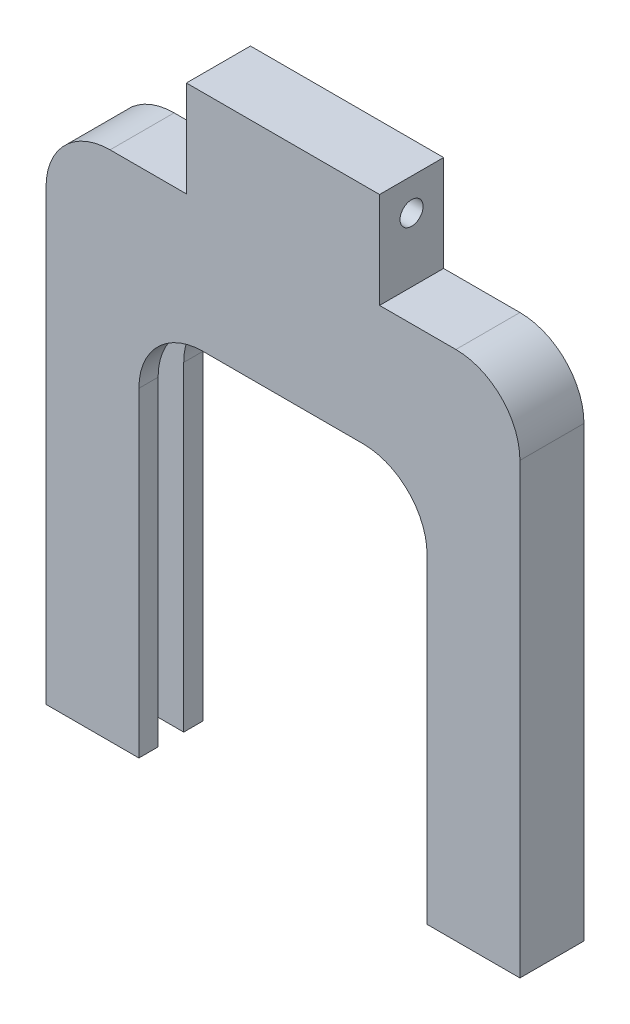
SolidWorks part; units mm, degrees
ref_plane "Alzado" through (0, 0, 0) normal (0, 0, 1) x (1, 0, 0)
ref_plane "Planta" through (0, 0, 0) normal (0, 1, 0) x (1, 0, 0)
ref_plane "Vista lateral" through (0, 0, 0) normal (1, 0, 0) x (0, 0, -1)
sketch "Croquis1" plane through (0, 0, 0) normal (0, 0, 1) x (1, 0, 0)
  line L1 (-37, 40) -> (37, 40)
  line L2 (-37, 40) -> (-37, -40)
  line L3 (-37, -40) -> (37, -40)
  line L4 (37, 40) -> (37, -40)
  line L5 (-37, 40) -> (37, -40) construction
  line L6 (-37, -40) -> (37, 40) construction
  point P0 (0, 0)
extrude "Saliente-Extruir1" add sketch "Croquis1" along normal blind 10
sketch "Croquis2" plane through (0, -40, 0) normal (0, -1, 0) x (1, 0, 0)
  line L0 (0, 10) -> (0, 0) construction
  line L1 (-37, 10) -> (37, 10) construction
  line L2 (-37, 0) -> (37, 0) construction
  line L4 (-32.9, 3) -> (32.9, 3)
  line L5 (-32.9, 3) -> (-32.9, 7)
  line L6 (-32.9, 7) -> (32.9, 7)
  line L7 (32.9, 3) -> (32.9, 7)
  line L8 (-32.9, 3) -> (32.9, 7) construction
  line L9 (-32.9, 7) -> (32.9, 3) construction
  point P6 (0, 5)
extrude "Cortar-Extruir1" cut sketch "Croquis2" against normal blind 60
sketch "Croquis3" plane through (0, 0, 10) normal (0, 0, 1) x (1, 0, 0)
  line L0 (0, -40) -> (0, 20) construction
  line L1 (-37, -40) -> (37, -40) construction
  line L2 (22.5, 20) -> (-22.5, 20)
  line L3 (-22.5, 20) -> (-22.5, -40)
  line L4 (-22.5, -40) -> (22.5, -40)
  line L5 (22.5, -40) -> (22.5, 20)
  point P8 (0, 20)
extrude "Cortar-Extruir3" cut sketch "Croquis3" against normal blind 39
sketch "Croquis6" plane through (0, 40, 0) normal (0, 1, 0) x (1, 0, 0)
  line L0 (0, 0) -> (0, -10) construction
  line L1 (37, 0) -> (-37, 0) construction
  line L2 (37, -10) -> (-37, -10) construction
  line L4 (15.082, 0) -> (-15.082, 0)
  line L5 (15.082, 0) -> (15.082, -10)
  line L6 (15.082, -10) -> (-15.082, -10)
  line L7 (-15.082, 0) -> (-15.082, -10)
  line L8 (15.082, 0) -> (-15.082, -10) construction
  line L9 (15.082, -10) -> (-15.082, 0) construction
  point P6 (0, -5)
extrude "Saliente-Extruir3" add sketch "Croquis6" along normal blind 15
fillet "Redondeo1" radius 10 1 edges at (-37, 40, 5)
fillet "Redondeo2" radius 10 1 edges at (37, 40, 5)
sketch "Croquis7" plane through (-15.082, 0, 0) normal (-1, 0, 0) x (0, 0, 1)
  line L0 (5, 55) -> (5, 50) construction
  line L1 (0, 55) -> (10, 55) construction
  circle A0 centre (5, 50) radius 1.8
extrude "Cortar-Extruir5" cut sketch "Croquis7" against normal blind 32
fillet "Redondeo3" radius 10 1 edges at (-22.5, 20, 8.5)
fillet "Redondeo4" radius 10 1 edges at (-22.5, 20, 1.5)
fillet "Redondeo5" radius 10 1 edges at (22.5, 20, 8.5)
fillet "Redondeo6" radius 10 1 edges at (22.5, 20, 1.5)
